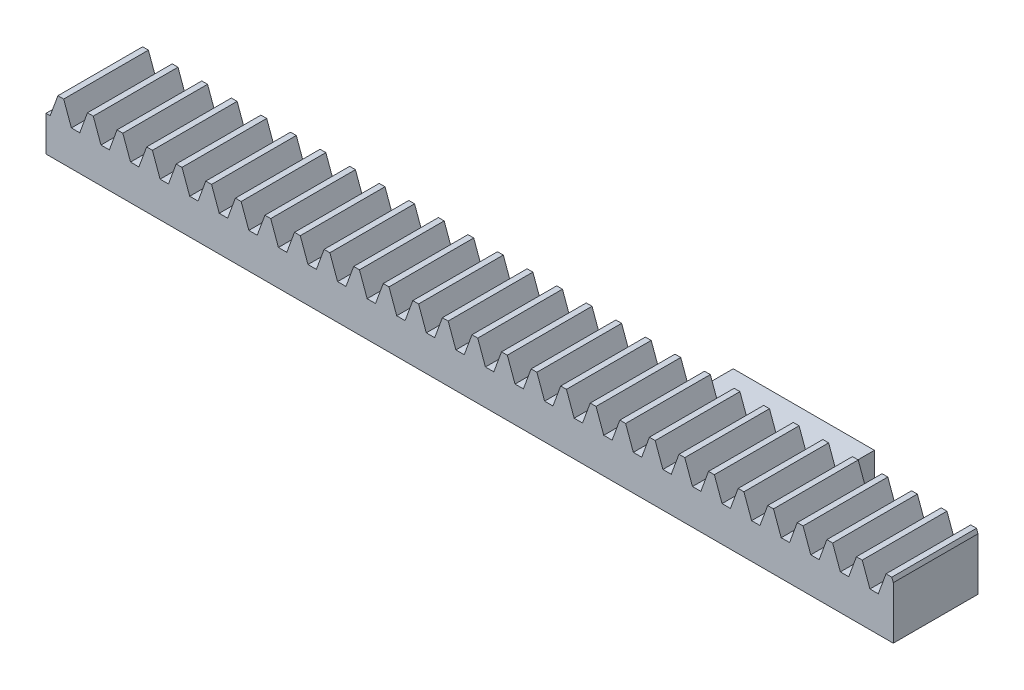
SolidWorks part; units mm, degrees
extrude "Blank" add sketch "BlankSke" against normal blind 12
sketch "BlankSke" plane through (0, 0, 0) normal (0, 0, 1) x (1, 0, 0)
  line L1 (0, 0) -> (90, 0)
  line L2 (0, 0) -> (0, 6)
  line L3 (0, 6) -> (90, 6)
  line L4 (90, 0) -> (90, 6)
  dimension "Length" = 90
  dimension "Blank_height" = 6
ref_plane "Plane1" through (0, 0, 0) normal (0, 0, 1) x (1, 0, 0)
ref_plane "Plane2" through (0, 0, 0) normal (0, 1, 0) x (1, 0, 0)
ref_plane "Plane3" through (0, 0, 0) normal (1, 0, 0) x (0, 0, -1)
sketch "HoldingSke" plane through (0, 0, 0) normal (0, 1, 0) x (1, 0, 0)
  line L0 (0, 0) -> (0.1392, 0.9903)
  line L1 (-15, 0) -> (100, 0) construction
  line L2 (0, 0) -> (-2.1039, 2.3779)
  line L3 (0, 0) -> (-11.863, 4.5341)
  line L4 (0, 0) -> (7.479, 4.318)
  line L5 (0, 0) -> (-23.7986, -8.8762)
  line L6 (0, 0) -> (-10.5278, -7.1032)
  line L9 (-71.009, 38.7566) -> (13.5634, 69.5384)
  line L10 (-76.2, 3.3779) -> (-71.2, 3.3779)
  line L11 (0, 0) -> (-12, 0)
  line L12 (-76.2, 101.6) -> (-76.162, 101.6)
  line L13 (24.9733, 27.94) -> (52.9518, 28.4284)
  line L14 (24.9733, 27.94) -> (24.9743, 27.94)
  line L15 (24.9733, 27.94) -> (100.4006, 29.5858)
  circle A0 centre (0, 0) radius 19.05
  circle A1 centre (0, 0) radius 2.5
  circle A2 centre (0, 0) radius 12.7
  dimension "MPH" = 5
  dimension "Diameter" = 38.1
  dimension "Num_teeth" = 30
  dimension "Pitch" = 1
  dimension "Show_teeth" = 998
  dimension "Thickness" = 12.7
  dimension "Ap" = 20
  dimension "Pitch_height" = 5
  dimension "Width" = 12
  dimension "Backlash" = 0.038
  dimension "Addendum_fac" = 1
  dimension "Dedendum_fac" = 1.25
  dimension "Clearance_fac" = 0.25
  dimension "Dedendum_add" = 0.001
  dimension "Length" = 90
  dimension "Module" = 1
sketch "TooCutSkeIll" plane through (0, 0, 0) normal (0, 0, 1) x (1, 0, 0)
  line L0 (-1.2538, 5.9737) -> (-0.5045, 3.9152)
  line L1 (-0.2687, 3.75) -> (0.2687, 3.75)
  line L2 (0.5045, 3.9152) -> (1.2538, 5.9737)
  line L3 (90, 6) -> (0, 6) construction
  line L4 (0, 0) -> (0, 64.897) construction
  line L5 (-13.208, 5) -> (12.954, 5) construction
  line L6 (0, 0) -> (90, 0) construction
  line L7 (0.8994, 5) -> (0.8994, 48.7463) construction
  line L8 (-0.8994, 5) -> (-0.8994, 48.7463) construction
  line L9 (1.2914, 6) -> (1.2914, 6.0254)
  line L10 (-1.2914, 6) -> (-1.2914, 6.0254)
  line L11 (-1.2914, 6.0254) -> (1.2914, 6.0254)
  arc A0 (0.2687, 3.75) -> (0.5045, 3.9152) centre (0.2687, 4.001) ccw
  arc A1 (-0.5045, 3.9152) -> (-0.2687, 3.75) centre (-0.2687, 4.001) ccw
  arc A2 (1.2914, 6) -> (1.2538, 5.9737) centre (1.2914, 5.96) ccw
  arc A3 (-1.2538, 5.9737) -> (-1.2914, 6) centre (-1.2914, 5.96) ccw
  dimension "Pitch_height" = 5
  dimension "Addendum_plus" = 1.0254
  dimension "Pressure_angle" = 20
  dimension "Gap_width" = 1.7988
  dimension "Dedendum" = 1.25
extrude "ToothCutIll" [suppressed] cut sketch "TooCutSkeIll" against normal through all
sketch "TooCutSkeSim" plane through (0, 0, 0) normal (0, 0, 1) x (1, 0, 0)
  line L0 (0.4444, 3.75) -> (-0.4444, 3.75)
  line L1 (1.2726, 6.0254) -> (0.4444, 3.75)
  line L2 (0, 17.4625) -> (0, 53.467) construction
  line L3 (1.2726, 6.0254) -> (-1.2726, 6.0254)
  line L6 (-1.2726, 6.0254) -> (-0.4444, 3.75)
  line L9 (-0.8994, 5) -> (0.8994, 5) construction
  line L10 (0, 0) -> (90, 0) construction
  line L11 (0.8994, 5) -> (0.8994, 53.467) construction
  line L12 (-0.8994, 5) -> (-0.8994, 53.467) construction
  dimension "Pitch_height" = 5
  dimension "Addendum_plus" = 1.0254
  dimension "Pressure_angle" = 20
  dimension "Gap_width" = 1.7988
  dimension "Dedendum" = 1.25
extrude "ToothCutSim" cut sketch "TooCutSkeSim" against normal through all
pattern_linear "TeethCuts" count 29 spacing 3.1416 along (1, 0, 0) of "ToothCutIll", "ToothCutSim"
sketch "Sketch3" plane through (0, 0, 0) normal (0, 1, 0) x (1, 0, 0)
  line L1 (0, 12) -> (91.4938, 12)
  line L2 (0, 12) -> (0, 9)
  line L3 (0, 9) -> (91.4938, 9)
  line L4 (91.4938, 12) -> (91.4938, 9)
  dimension "D1" = 3
extrude "Cut-Extrude3" cut sketch "Sketch3" along normal blind 10
sketch "Sketch4" plane through (0, 0, -9) normal (0, 0, -1) x (-1, 0, 0)
  line L0 (0, 0) -> (-90, 0) construction
  line L1 (-75, 0) -> (-60, 0)
  line L2 (-75, 0) -> (-75, 3.75)
  line L3 (-75, 3.75) -> (-60, 3.75)
  line L4 (-60, 0) -> (-60, 3.75)
  line L5 (0, 3.75) -> (0, 0) construction
  dimension "D1" = 60
  dimension "D2" = 15
extrude "Boss-Extrude1" add sketch "Sketch4" along normal blind 4
equation "' \"Module@HoldingSke\" = 6.35"
equation "' \"Num_teeth@HoldingSke\" = 12"
equation "' \"Ap@HoldingSke\" =  20"
equation "' \"Ap@HoldingSke\" = 20"
equation "' \"Width@HoldingSke\" = 0.25 * 25.4"
equation "' \"Show_teeth@HoldingSke\" = 500"
equation "' \"Backlash@HoldingSke\" = 0.009 * 25.4"
equation "' \"Addendum_fac@HoldingSke\" = 1.0"
equation "' \"Dedendum_fac@HoldingSke\" = 1.25"
equation "' \"Dedendum_add@HoldingSke\" = 0.00005 * 25.4"
equation "' \"Clearance_fac@HoldingSke\" = 0.25"
equation "' \"Pitch_height@HoldingSke\" = 1 * 25.4"
equation "' \"Length@HoldingSke\" = 4.71 * 25.4"
equation "\"Pitch@HoldingSke\" = 1 / \"Module@HoldingSke\""
equation "\"MPH@HoldingSke\" = \"Dedendum_fac@HoldingSke\" / \"Pitch@HoldingSke\" + 2 * \"Dedendum_add@HoldingSke\" + 0.002 * 25.4"
equation "\"MPH@HoldingSke\" = ((sgn( \"MPH@HoldingSke\" - \"Pitch_height@HoldingSke\")+1)*( \"MPH@HoldingSke\" - \"Pitch_height@HoldingSke\"))/2 + \"Pitch_height@HoldingSke\""
equation "\"Blank_height@BlankSke\" = \"Pitch_height@HoldingSke\" + \"Addendum_fac@HoldingSke\"  / \"Pitch@HoldingSke\" "
equation "\"Length@BlankSke\" =  \"Length@HoldingSke\""
equation "\"Face_width@Blank\" = \"Width@HoldingSke\""
equation "\"Pressure_angle@TooCutSkeIll\" = \"Ap@HoldingSke\""
equation "\"Addendum_plus@TooCutSkeIll\" =  \"Addendum_fac@HoldingSke\"  / \"Pitch@HoldingSke\" + 0.001 *25.4"
equation "\"Dedendum@TooCutSkeIll\" = \"Dedendum_fac@HoldingSke\"  / \"Pitch@HoldingSke\""
equation "\"Pitch_height@TooCutSkeIll\" =  \"MPH@HoldingSke\""
equation "\"Gap_width@TooCutSkeIll\" = 3.14159265 / 2 / \"Pitch@HoldingSke\" + 6 * \"Backlash@HoldingSke\""
equation "\"Pressure_angle@TooCutSkeSim\" = \"Ap@HoldingSke\""
equation "\"Addendum_plus@TooCutSkeSim\" =  \"Addendum_fac@HoldingSke\"  / \"Pitch@HoldingSke\" + 0.001 * 25.4"
equation "\"Dedendum@TooCutSkeSim\" = \"Dedendum_fac@HoldingSke\"  / \"Pitch@HoldingSke\""
equation "\"Pitch_height@TooCutSkeSim\" =  \"MPH@HoldingSke\""
equation "\"Gap_width@TooCutSkeSim\" = 3.14159265 / 2 / \"Pitch@HoldingSke\" + 6 * \"Backlash@HoldingSke\""
equation "\"Root_fillet@TooCutSkeIll\" = \"Clearance_fac@HoldingSke\" / \"Pitch@HoldingSke\" + \"Dedendum_add@HoldingSke\""
equation "\"Break_rad@TooCutSkeIll\" = 0.02 / \"Pitch@HoldingSke\" * 2"
equation "\"Linear_pitch@TeethCuts\" = 3.14159265 / \"Pitch@HoldingSke\""
equation "\"Num_teeth@HoldingSke\" = int( ( \"Length@HoldingSke\" + 0 ) / (3.14159265 / \"Pitch@HoldingSke\")) + 0.9999  + 1"
equation " \"Num_teeth@TeethCuts\" = int( \"Show_teeth@HoldingSke\" ) + 1"
equation " \"Num_teeth@TeethCuts\" = ((sgn( \"Num_teeth@TeethCuts\" - \"Num_teeth@HoldingSke\" )-1)*( \"Num_teeth@TeethCuts\" - \"Num_teeth@HoldingSke\" ))/-2+ \"Num_teeth@HoldingSke\""
equation " \"Num_teeth@TeethCuts\" = ((sgn( \"Num_teeth@TeethCuts\" - 2.0)+1)*( \"Num_teeth@TeethCuts\" - 2.0))/2 +2.0"
